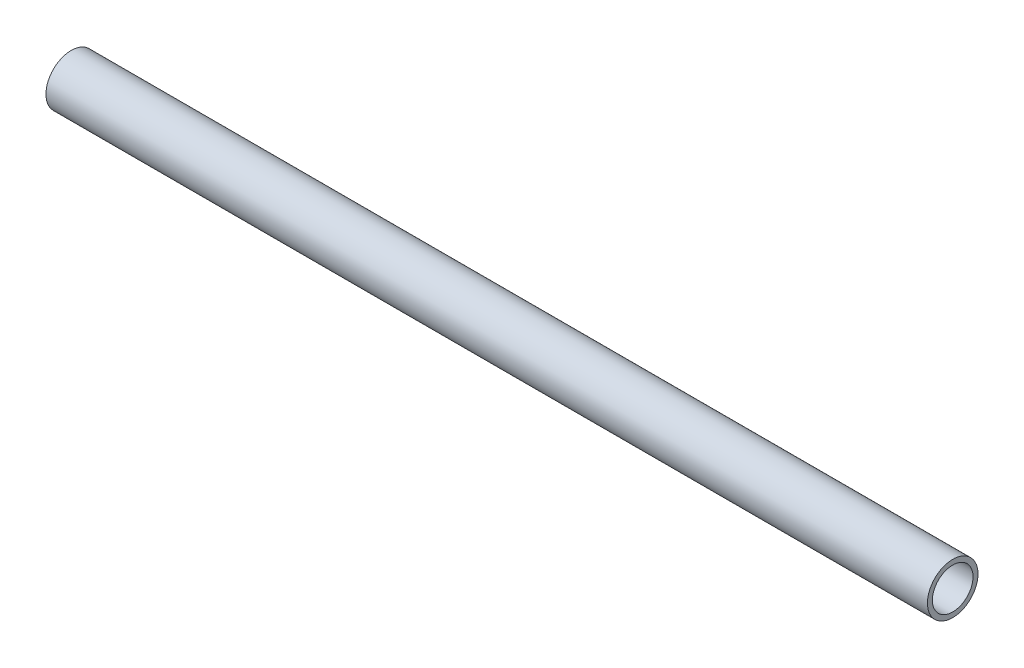
SolidWorks part; units mm, degrees
ref_plane "Vorne" through (0, 0, 0) normal (0, 0, 1) x (1, 0, 0)
ref_plane "Oben" through (0, 0, 0) normal (0, 1, 0) x (1, 0, 0)
ref_plane "Seite" through (0, 0, 0) normal (1, 0, 0) x (0, 0, -1)
sketch "Skizze1" plane through (0, 0, 0) normal (1, 0, 0) x (0, 0, -1)
  circle A0 centre (0, 0) radius 2.05
  circle A1 centre (0, 0) radius 2.55
  dimension "D1" = 4.1
  dimension "D2" = 5.1
extrude "Aufsatz-Linear austragen1" add sketch "Skizze1" along normal blind 88.9
